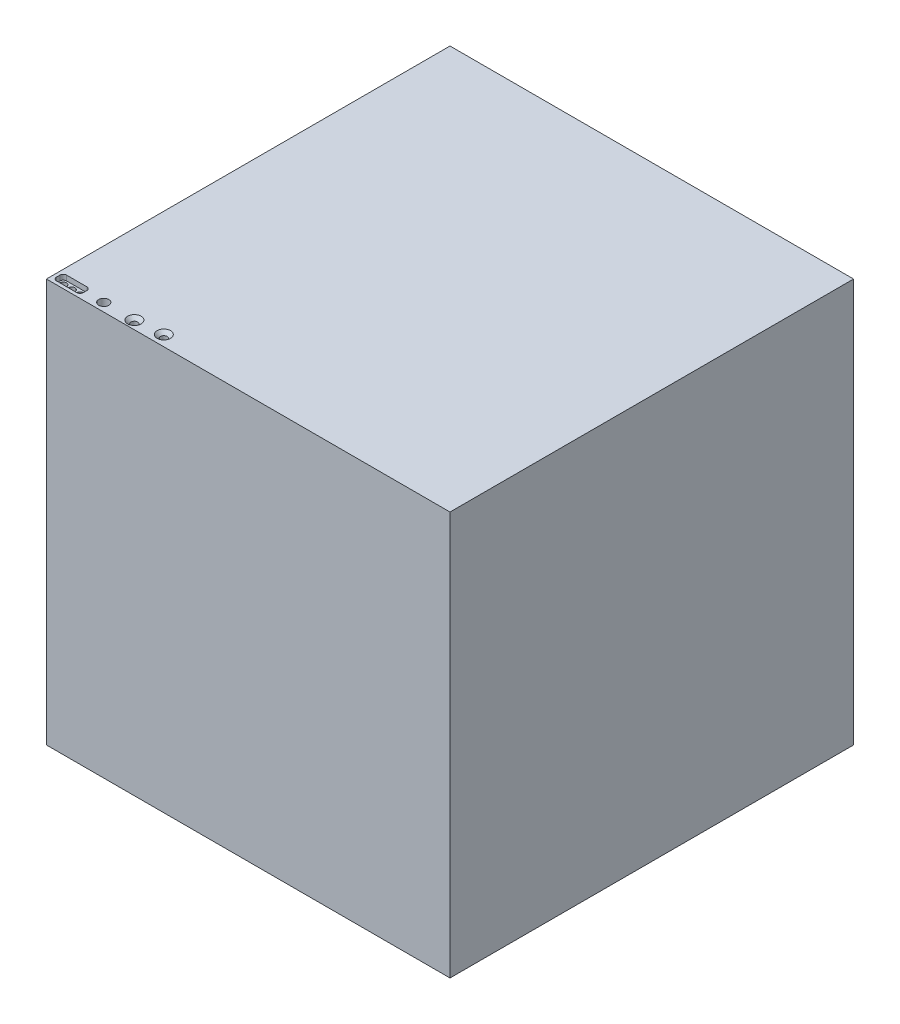
SolidWorks part; units mm, degrees
material "Steel, Hot Worked, AISI 1095"
ref_plane "Front Plane" through (0, 0, 0) normal (0, 0, 1) x (1, 0, 0)
ref_plane "Top Plane" through (0, 0, 0) normal (0, 1, 0) x (1, 0, 0)
ref_plane "Right Plane" through (0, 0, 0) normal (1, 0, 0) x (0, 0, -1)
sketch "Sketch1" plane through (0, 0, 0) normal (0, 1, 0) x (1, 0, 0)
  line L1 (0, 0) -> (1200, 0)
  line L2 (0, 0) -> (0, 1200)
  line L3 (0, 1200) -> (1200, 1200)
  line L4 (1200, 0) -> (1200, 1200)
  dimension "D1" = 1200
  dimension "D2" = 1200
extrude "Boss-Extrude1" add sketch "Sketch1" along normal blind 1200
sketch "Sketch3" plane through (0, 1200, 0) normal (0, 1, 0) x (1, 0, 0)
  line L0 (0, 1200) -> (0, 0) construction
  line L1 (10, 10) -> (90, 10)
  line L2 (10, 10) -> (10, 40)
  line L3 (10, 40) -> (90, 40)
  line L4 (90, 10) -> (90, 40)
  line L5 (0, 0) -> (1200, 0) construction
  dimension "D1" = 10
  dimension "D2" = 80
  dimension "D3" = 10
  dimension "D4" = 30
extrude "Cut-Extrude2" cut sketch "Sketch3" against normal blind 15
fillet "Fillet1" radius 10 4 edges at (90, 1192.5, -10) (90, 1192.5, -40) (10, 1192.5, -40) (10, 1192.5, -10)
sketch "Sketch4" plane through (0, 1185, 0) normal (0, 1, 0) x (1, 0, 0)
  line L0 (0, 1200) -> (0, 0) construction
  line L1 (0, 0) -> (1200, 0) construction
  circle A0 centre (25, 25) radius 10
  circle A2 centre (75, 25) radius 10
  dimension "D1" = 20
  dimension "D2" = 50
  dimension "D4" = 25
  dimension "D5" = 25
extrude "Cut-Extrude3" cut sketch "Sketch4" against normal blind 15
sketch "Sketch5" plane through (0, 1185, 0) normal (0, 1, 0) x (1, 0, 0)
  line L0 (0, 0) -> (1200, 0) construction
  circle A0 centre (50, 25) radius 10
  circle A2 centre (25, 25) radius 10 construction
  dimension "D1" = 20
  dimension "D2" = 25
  dimension "D3" = 25
extrude "Cut-Extrude4" cut sketch "Sketch5" against normal through all
sketch "Sketch6" plane through (0, 1200, 0) normal (0, 1, 0) x (1, 0, 0)
  circle A0 centre (145.5001, 25) radius 15
  dimension "D1" = 30
extrude "Cut-Extrude5" cut sketch "Sketch6" against normal blind 100
sketch "Sketch8" plane through (0, 1100, 0) normal (0, 1, 0) x (1, 0, 0)
  circle A0 centre (145.5001, 25) radius 7.5
  dimension "D1" = 15
extrude "Cut-Extrude6" cut sketch "Sketch8" against normal blind 100
sketch "Sketch11" plane through (0, 1200, 0) normal (0, 1, 0) x (1, 0, 0)
  circle A0 centre (236.4653, 25) radius 10
  dimension "D1" = 20
extrude "Cut-Extrude7" cut sketch "Sketch11" against normal blind 250
chamfer "Chamfer1" distance 10 angle 45 1 edges at (236.4653, 1200, -15)
sketch "Sketch12" plane through (0, 1200, 0) normal (0, 1, 0) x (1, 0, 0)
  circle A0 centre (317.3981, 31.6121) radius 10
  dimension "D1" = 20
extrude "Cut-Extrude8" cut sketch "Sketch12" against normal blind 30.004
chamfer "Chamfer2" distance 10 angle 45 1 edges at (317.3981, 1200, -21.6121)
